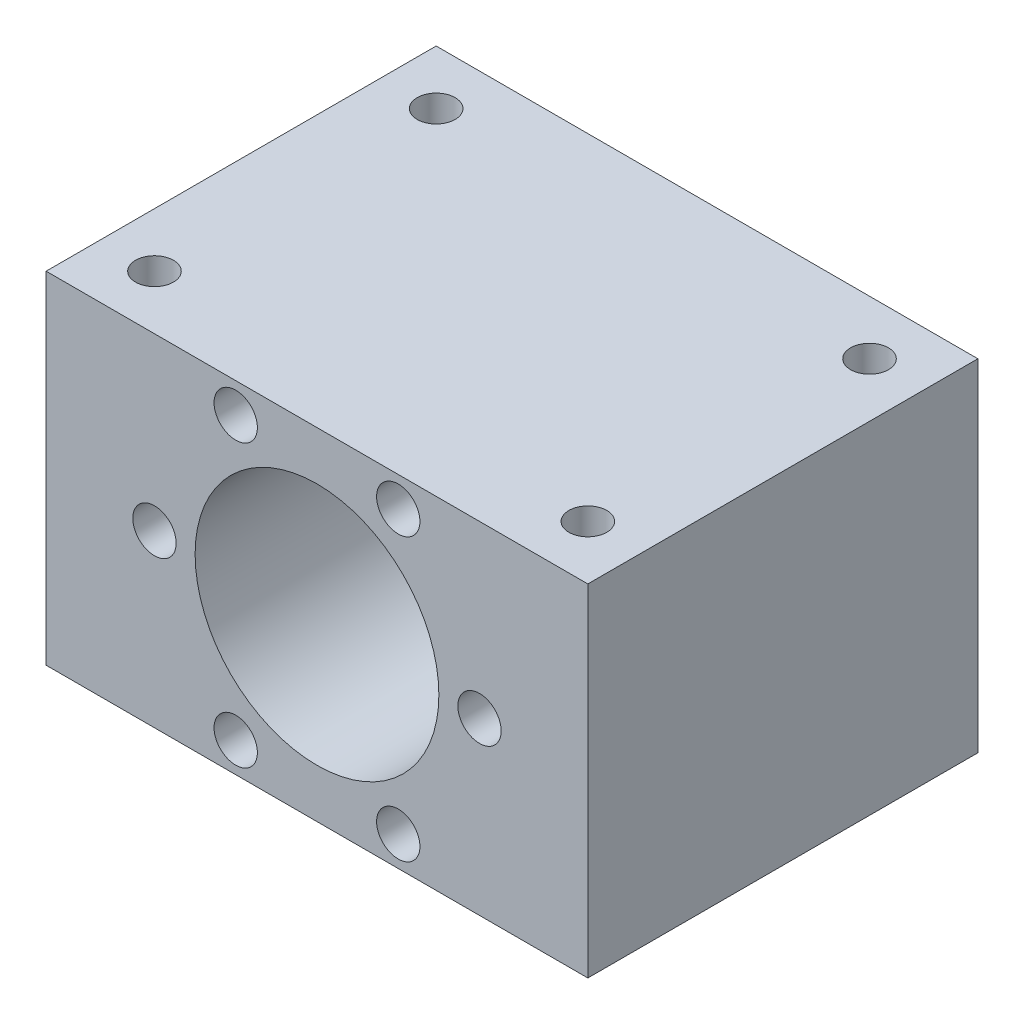
SolidWorks part; units mm, degrees
ref_plane "Alzado" through (0, 0, 0) normal (0, 0, 1) x (1, 0, 0)
ref_plane "Planta" through (0, 0, 0) normal (0, 1, 0) x (1, 0, 0)
ref_plane "Vista lateral" through (0, 0, 0) normal (1, 0, 0) x (0, 0, -1)
sketch "Croquis1" plane through (0, 0, 0) normal (0, 0, 1) x (1, 0, 0)
  line L1 (-25, -15.75) -> (25, -15.75)
  line L2 (-25, -15.75) -> (-25, 15.75)
  line L3 (-25, 15.75) -> (25, 15.75)
  line L4 (25, -15.75) -> (25, 15.75)
  line L5 (-25, -15.75) -> (25, 15.75) construction
  line L6 (-25, 15.75) -> (25, -15.75) construction
  circle A0 centre (0, 0) radius 11.25
  point P0 (0, 0)
  dimension "D3" = 22.5
  dimension "D1" = 50
  dimension "D2" = 31.5
extrude "Saliente-Extruir1" add sketch "Croquis1" along normal blind 36
sketch "Croquis2" plane through (0, 15.75, 0) normal (0, 1, 0) x (1, 0, 0)
  line L0 (-25, -36) -> (-25, 0) construction
  line L1 (25, 0) -> (-25, 0) construction
  circle A0 centre (-20, -5) radius 1.75
  circle A1 centre (20, -5) radius 1.75
  circle A2 centre (20, -31) radius 1.75
  circle A3 centre (-20, -31) radius 1.75
  point P8 (0, 0)
  point P9 (0, 0)
  point P10 (0, 0)
  point P11 (0, 0)
  point P12 (0, 0)
  dimension "D1" = 5
  dimension "D2" = 5
  dimension "D3" = 40
  dimension "D4" = 26
  dimension "D5" = 3.5
extrude "Cortar-Extruir1" cut sketch "Croquis2" against normal blind 10
sketch "Croquis3" plane through (0, 0, 36) normal (0, 0, 1) x (1, 0, 0)
  circle A1 centre (-15, 0) radius 2
  dimension "D1" = 4
  dimension "D2" = 15
extrude "Cortar-Extruir2" cut sketch "Croquis3" against normal blind 18
pattern_circular "MatrizC1" count 6 over 360 about axis through (0, 0, 0) along (0, 0, 1) of "Cortar-Extruir2"
